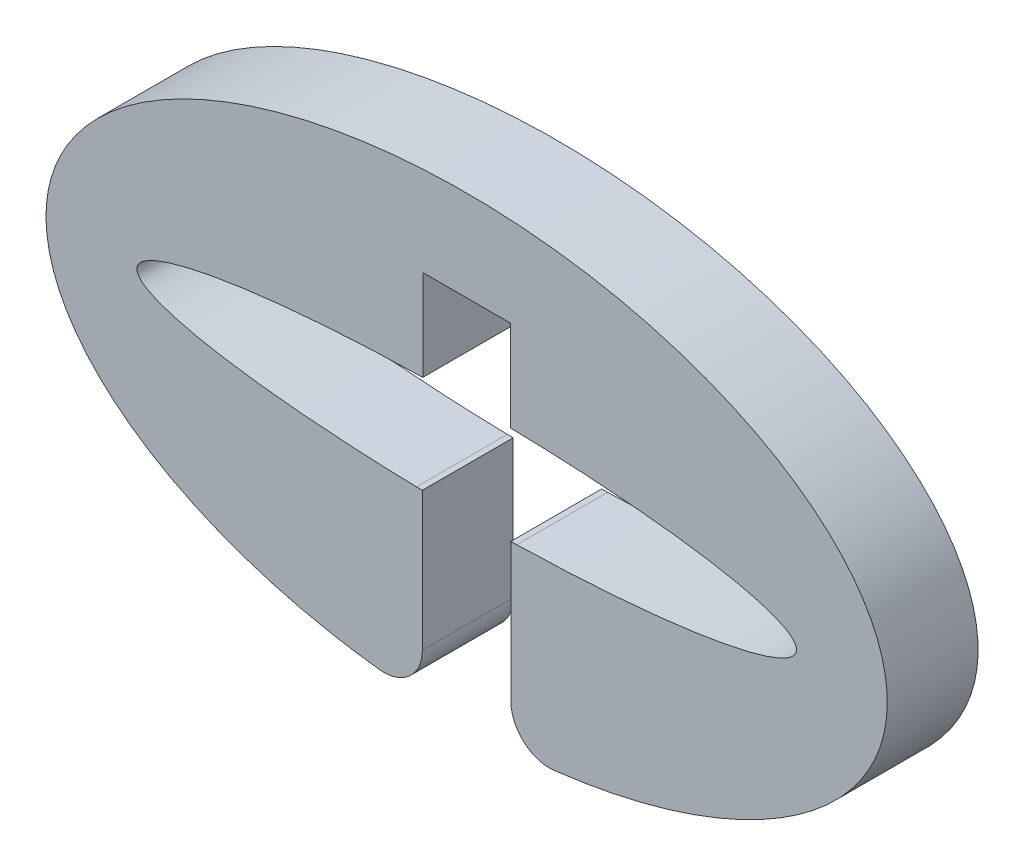
SolidWorks part; units mm, degrees
material "Acrylic (Medium-high impact)"
ref_plane "Front Plane" through (0, 0, 0) normal (0, 0, 1) x (1, 0, 0)
ref_plane "Top Plane" through (0, 0, 0) normal (0, 1, 0) x (1, 0, 0)
ref_plane "Right Plane" through (0, 0, 0) normal (1, 0, 0) x (0, 0, -1)
sketch "스케치1" plane through (0, 0, 0) normal (0, 0, 1) x (1, 0, 0)
  line L0 (0, 10.85) -> (0, 0) construction
  line L7 (0, 0) -> (0, -4.8281) construction
  line L8 (-1.3783, -7.5227) -> (1.2141, -7.5227) construction
  line L10 (-1.3783, -2.1335) -> (1.3783, -2.1335) construction
  line L12 (-1.3783, -7.5227) -> (1.3783, -2.1335) construction
  line L13 (-1.3783, -2.1335) -> (1.2141, -7.5227) construction
  line L15 (-1.875, 1.7135) -> (1.875, 1.7135) construction
  line L17 (0, -4.7676) -> (0, 0) construction
  line L18 (-1.4475, 1.62) -> (1.4475, 1.62) construction
  line L19 (-13.5575, -7.5227) -> (13.5575, -7.5227) construction
  line L23 (-13.5575, -7.5227) -> (13.5575, 8.3308) construction
  line L24 (-13.5575, 8.3308) -> (13.5575, -7.5227) construction
  line L26 (-1.4475, 1.62) -> (-1.4475, 4.62)
  line L27 (-1.4475, 4.62) -> (1.4475, 4.62)
  line L28 (1.4475, 1.62) -> (1.4475, 4.62)
  line L29 (-1.4475, 1.62) -> (1.4475, 4.62) construction
  line L30 (-1.4475, 4.62) -> (1.4475, 1.62) construction
  line L31 (-1.5, -7.62) -> (1.5, -7.62) construction
  line L32 (-1.6577, -7.5656) -> (-1.6577, -1.6155) construction
  line L33 (-1.6577, -1.6155) -> (1.6577, -1.6155)
  line L34 (1.6577, -7.5656) -> (1.6577, -1.6155) construction
  line L35 (-1.5, -7.62) -> (1.6577, -1.6155) construction
  line L36 (-1.6577, -1.6155) -> (1.5, -7.62) construction
  circle A0 centre (0, 0) radius 7.62 construction
  circle A1 centre (0, 0) radius 2.54 construction
  arc A2 (-1.3783, -7.5227) -> (1.2141, -7.5227) centre (-0.0821, 0.5087) cw construction
  arc A3 (-1.6577, -7.5656) -> (1.6577, -7.5656) centre (0, 18.8937) ccw
  ellipse E0 centre (0, 0) end of major axis (-13.8962, 0) minor radius 7.62 (1.6577, -7.5656) -> (-1.6577, -7.5656) ccw
  ellipse E1 centre (0, 0) end of major axis (-10.8962, 0) minor radius 1.6345 (-1.4475, 1.62) -> (-1.6577, -1.6155) ccw
  ellipse E2 centre (0, 0) end of major axis (-10.8962, 0) minor radius 1.6345 (1.6577, -1.6155) -> (1.4475, 1.62) ccw
  point P2 (0, 10.85)
  point P5 (0, 2.8708)
  point P7 (0, 3.12)
  point P10 (-0.0423, -4.9108)
  point P30 (0, -4.7676)
  dimension "D1" = 5.08
  dimension "D2" = 5.08
  dimension "D6" = 2.895
  dimension "D3" = 3
  dimension "D4" = 3
  dimension "D5" = 2.5925
  dimension "D7" = 3
  dimension "D8" = 3
extrude "보스-돌출1" add sketch "스케치1" along normal blind 3
sketch "스케치2" plane through (0, 0, 3) normal (0, 0, 1) x (1, 0, 0)
  line L0 (0, -6.2297) -> (0, 0) construction
  line L1 (-1.4625, -11.6091) -> (1.4625, -11.6091)
  line L2 (-1.4625, -11.6091) -> (-1.4625, -0.8503)
  line L3 (-1.4625, -0.8503) -> (1.4625, -0.8503)
  line L4 (1.4625, -11.6091) -> (1.4625, -0.8503)
  line L5 (-1.4625, -11.6091) -> (1.4625, -0.8503) construction
  line L6 (-1.4625, -0.8503) -> (1.4625, -11.6091) construction
  point P0 (0, -6.2297)
  dimension "D1" = 2.925
extrude "컷-돌출1" cut sketch "스케치2" against normal up to surface (3 mm away) up to face at (0, 0.0013, 0)
fillet "필렛1" radius 1.27 2 edges at (-1.4625, -7.5771, 1.5) (1.4625, -7.5771, 1.5)
